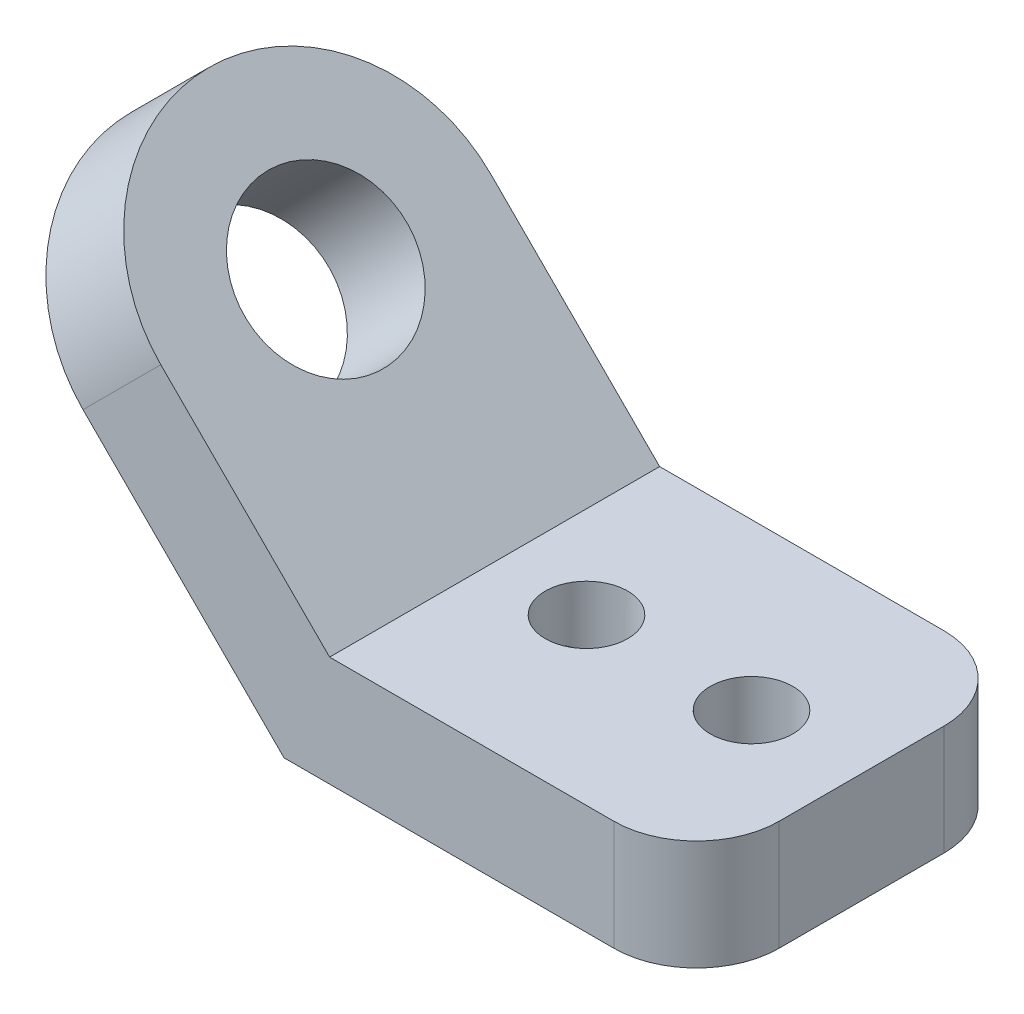
SolidWorks part; units mm, degrees
ref_plane "Alzado" through (0, 0, 0) normal (0, 0, 1) x (1, 0, 0)
ref_plane "Planta" through (0, 0, 0) normal (0, 1, 0) x (1, 0, 0)
ref_plane "Vista lateral" through (0, 0, 0) normal (1, 0, 0) x (0, 0, -1)
sketch "Croquis2" plane through (0, 0, 0) normal (0, 1, 0) x (1, 0, 0)
  line L0 (-2.585, 3) -> (2.585, 3)
  line L1 (4.085, 1.5) -> (4.085, -1.5)
  line L2 (2.585, -3) -> (-2.585, -3)
  line L3 (-2.585, 3) -> (-2.585, -3)
  arc A0 (2.585, 3) -> (4.085, 1.5) centre (2.585, 1.5) cw
  arc A1 (4.085, -1.5) -> (2.585, -3) centre (2.585, -1.5) cw
  circle A2 centre (-0.915, 0) radius 0.75
  circle A3 centre (2.085, 0) radius 0.75
  point P12 (0, 0)
  point P13 (4.085, 0)
  point P14 (0, 0)
  point P15 (0, 0)
  point P16 (0, 0)
  point P18 (0, 3)
  dimension "D1" = 1.5
  dimension "D3" = 1.5
  dimension "D2" = 3
  dimension "D4" = 3
  dimension "D5" = 2
  dimension "D6" = 4.67
extrude "Saliente-Extruir1" add sketch "Croquis2" along normal blind 2
ref_plane "Plano3" through (-0.2925, -0.2925, 0) normal (0.7071, 0.7071, 0) x (0, 0, 1)
sketch "Croquis6" plane through (-0.2925, -0.2925, 0) normal (0.7071, 0.7071, 0) x (0, 0, 1)
  line L1 (-3, -3.2421) -> (3, -3.2421)
  line L2 (-3, -3.2421) -> (-3, -7.5821)
  line L4 (3, -3.2421) -> (3, -7.5821)
  arc A0 (-3, -7.5821) -> (3, -7.5821) centre (0, -7.5821) ccw
  circle A1 centre (0, -7.5821) radius 1.475
  dimension "D1" = 4.34
  dimension "D2" = 2.95
extrude "Saliente-Extruir3" add sketch "Croquis6" against normal blind 2 separate body
sketch "Croquis8" plane through (-2.2925, 2.2925, 0) normal (0.7071, -0.7071, 0) x (0, 0, -1)
  line L1 (-3, -2.4137) -> (3, -2.4137)
  line L2 (-3, -2.4137) -> (-3, -0.4137)
  line L3 (-3, -0.4137) -> (3, -0.4137)
  line L4 (3, -2.4137) -> (3, -0.4137)
extrude "Saliente-Extruir4" add sketch "Croquis8" along normal up to surface (0.8284 mm away)
